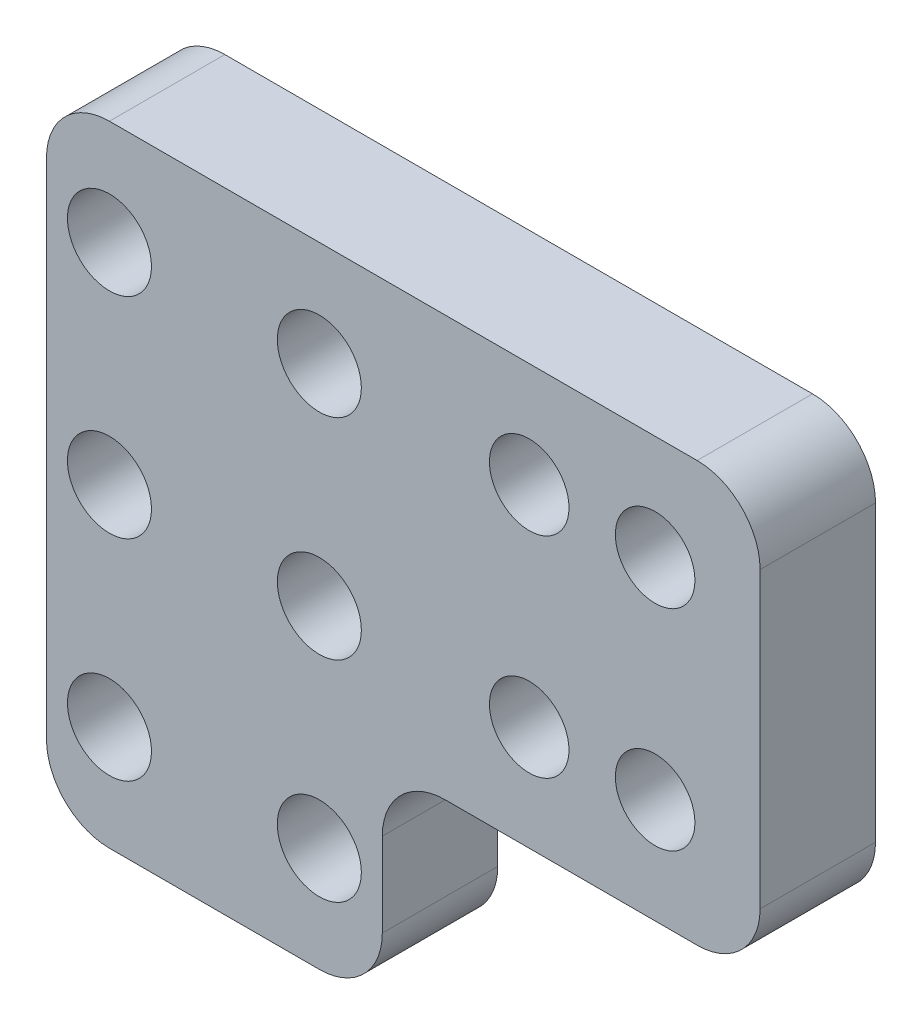
SolidWorks part; units mm, degrees
ref_plane "前视基准面" through (0, 0, 0) normal (0, 0, 1) x (1, 0, 0)
ref_plane "上视基准面" through (0, 0, 0) normal (0, 1, 0) x (1, 0, 0)
ref_plane "右视基准面" through (0, 0, 0) normal (1, 0, 0) x (0, 0, -1)
other "Configuration Table"
sketch "草图1" plane through (0, 0, 0) normal (0, 0, 1) x (1, 0, 0)
  line L1 (-8, 15) -> (8, 15)
  line L2 (-8, 15) -> (-8, -15)
  line L3 (-8, -15) -> (8, -15)
  line L4 (8, -5) -> (8, -15)
  line L5 (-8, 15) -> (8, -15) construction
  line L6 (-8, -15) -> (8, 15) construction
  line L7 (26, -5) -> (8, -5)
  line L8 (26, -5) -> (26, 15)
  line L9 (26, 15) -> (8, 15)
  line L11 (26, -5) -> (8, 15) construction
  line L12 (26, 15) -> (8, -5) construction
  circle A0 centre (-5, 10) radius 2.0017
  circle A1 centre (5, 10) radius 2.0017
  circle A2 centre (5, 0) radius 2.0017
  circle A3 centre (5, -10) radius 2.0017
  circle A4 centre (-5, 0) radius 2.0017
  circle A5 centre (-5, -10) radius 2.0017
  circle A6 centre (15, 10) radius 1.8951
  circle A7 centre (21, 10) radius 1.8951
  circle A8 centre (21, 0) radius 1.8951
  circle A9 centre (15, 0) radius 1.8951
  point P0 (0, 0)
  point P6 (17, 5)
  dimension "D6" = 3
  dimension "D7" = 5
  dimension "D11" = 10
  dimension "D1" = 16
  dimension "D2" = 20
  dimension "D3" = 30
  dimension "D8" = 18
  dimension "D4" = 2
  dimension "D5" = 3
  dimension "D9" = 2
  dimension "D10" = 2
extrude "凸台-拉伸1" add sketch "草图1" along normal blind 5.5
fillet "圆角1" radius 3 6 edges at (8, -15, 2.75) (26, 15, 2.75) (26, -5, 2.75) (8, -5, 2.75) (-8, -15, 2.75) (-8, 15, 2.75)
sketch "草图2" plane through (0, 0, 0) normal (0, 0, -1) x (-1, 0, 0)
  line L0 (-21, 10) -> (-15, 10) construction
  line L1 (-18, 15) -> (-18, -5)
  line L2 (-23, 15) -> (5, 15) construction
  line L3 (-11, -5) -> (-23, -5) construction
  line L10 (-8, -8) -> (-8, -12)
  line L11 (-5, -15) -> (5, -15)
  line L12 (8, -12) -> (8, 12)
  line L13 (5, 15) -> (-23, 15)
  line L14 (-26, 12) -> (-26, -2)
  line L15 (-23, -5) -> (-11, -5)
  line L19 (-18, 15) -> (-23, 15)
  line L20 (-26, 12) -> (-26, -2)
  line L21 (-23, -5) -> (-18, -5)
  arc A6 (-8, -12) -> (-5, -15) centre (-5, -12) ccw
  arc A7 (5, -15) -> (8, -12) centre (5, -12) ccw
  arc A8 (8, 12) -> (5, 15) centre (5, 12) ccw
  arc A9 (-23, 15) -> (-26, 12) centre (-23, 12) ccw
  arc A10 (-26, -2) -> (-23, -5) centre (-23, -2) ccw
  arc A11 (-8, -8) -> (-11, -5) centre (-11, -8) ccw
  arc A15 (-23, 15) -> (-26, 12) centre (-23, 12) ccw
  arc A16 (-26, -2) -> (-23, -5) centre (-23, -2) ccw
  dimension "D1" = 0
